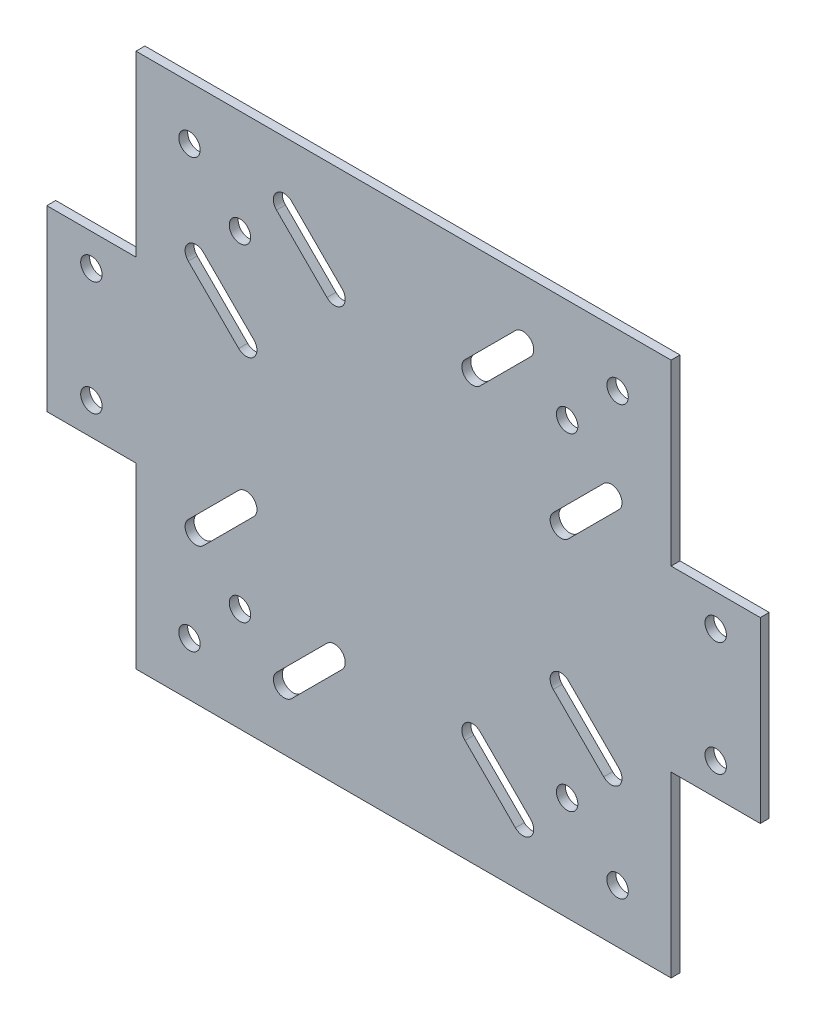
SolidWorks part; units mm, degrees
ref_plane "Front Plane" through (0, 0, 0) normal (0, 0, 1) x (1, 0, 0)
ref_plane "Top Plane" through (0, 0, 0) normal (0, 1, 0) x (1, 0, 0)
ref_plane "Right Plane" through (0, 0, 0) normal (1, 0, 0) x (0, 0, -1)
sketch "Sketch1" plane through (0, 0, 0) normal (0, 0, 1) x (1, 0, 0)
  line L0 (-91.7157, 91.7157) -> (-87.4731, 95.9584) construction
  line L1 (-150, 150) -> (150, 150)
  line L2 (-150, 150) -> (-150, -150)
  line L3 (-150, -150) -> (150, -150)
  line L4 (150, 150) -> (150, -150)
  line L5 (-150, 150) -> (150, -150) construction
  line L6 (-150, -150) -> (150, 150) construction
  line L9 (-87.4731, 95.9584) -> (-95.9584, 87.4731) construction
  line L14 (-116.4645, 66.967) -> (-150, 33.4315) construction
  line L27 (-87.4731, 95.9584) -> (-33.4315, 150) construction
  line L28 (-66.967, 116.4645) -> (-38.6827, 88.1802) construction
  line L29 (-62.7244, 120.7071) -> (-34.4401, 92.4228)
  line L30 (-71.2096, 112.2218) -> (-42.9254, 83.9376)
  line L31 (66.967, 116.4645) -> (38.6827, 88.1802) construction
  line L32 (71.2096, 112.2218) -> (42.9254, 83.9376)
  line L33 (-116.4645, 66.967) -> (-88.1802, 38.6827) construction
  line L34 (-112.2218, 71.2096) -> (-83.9376, 42.9254)
  line L35 (-120.7071, 62.7244) -> (-92.4228, 34.4401)
  line L36 (62.7244, 120.7071) -> (34.4401, 92.4228)
  line L37 (116.4645, 66.967) -> (88.1802, 38.6827) construction
  line L38 (120.7071, 62.7244) -> (92.4228, 34.4401)
  line L39 (112.2218, 71.2096) -> (83.9376, 42.9254)
  line L40 (116.4645, -66.967) -> (88.1802, -38.6827) construction
  line L41 (112.2218, -71.2096) -> (83.9376, -42.9254)
  line L42 (120.7071, -62.7244) -> (92.4228, -34.4401)
  line L43 (66.967, -116.4645) -> (38.6827, -88.1802) construction
  line L44 (62.7244, -120.7071) -> (34.4401, -92.4228)
  line L45 (71.2096, -112.2218) -> (42.9254, -83.9376)
  line L46 (-66.967, -116.4645) -> (-38.6827, -88.1802) construction
  line L47 (-71.2096, -112.2218) -> (-42.9254, -83.9376)
  line L48 (-62.7244, -120.7071) -> (-34.4401, -92.4228)
  line L49 (-116.4645, -66.967) -> (-88.1802, -38.6827) construction
  line L50 (-120.7071, -62.7244) -> (-92.4228, -34.4401)
  line L51 (-112.2218, -71.2096) -> (-83.9376, -42.9254)
  circle A0 centre (-120, 120) radius 6
  circle A1 centre (120, 120) radius 6
  circle A2 centre (-120, -120) radius 6
  circle A3 centre (120, -120) radius 6
  circle A4 centre (-91.7157, 91.7157) radius 6
  circle A5 centre (91.7157, 91.7157) radius 6
  circle A6 centre (-91.7157, -91.7157) radius 6
  circle A7 centre (91.7157, -91.7157) radius 6
  arc A24 (-62.7244, 120.7071) -> (-71.2096, 112.2218) centre (-66.967, 116.4645) ccw
  arc A25 (-42.9254, 83.9376) -> (-34.4401, 92.4228) centre (-38.6827, 88.1802) ccw
  arc A26 (-112.2218, 71.2096) -> (-120.7071, 62.7244) centre (-116.4645, 66.967) ccw
  arc A27 (71.2096, 112.2218) -> (62.7244, 120.7071) centre (66.967, 116.4645) ccw
  arc A28 (34.4401, 92.4228) -> (42.9254, 83.9376) centre (38.6827, 88.1802) ccw
  arc A29 (120.7071, 62.7244) -> (112.2218, 71.2096) centre (116.4645, 66.967) ccw
  arc A30 (83.9376, 42.9254) -> (92.4228, 34.4401) centre (88.1802, 38.6827) ccw
  arc A31 (-92.4228, 34.4401) -> (-83.9376, 42.9254) centre (-88.1802, 38.6827) ccw
  arc A32 (112.2218, -71.2096) -> (120.7071, -62.7244) centre (116.4645, -66.967) ccw
  arc A33 (92.4228, -34.4401) -> (83.9376, -42.9254) centre (88.1802, -38.6827) ccw
  arc A34 (62.7244, -120.7071) -> (71.2096, -112.2218) centre (66.967, -116.4645) ccw
  arc A35 (42.9254, -83.9376) -> (34.4401, -92.4228) centre (38.6827, -88.1802) ccw
  arc A36 (-71.2096, -112.2218) -> (-62.7244, -120.7071) centre (-66.967, -116.4645) ccw
  arc A37 (-34.4401, -92.4228) -> (-42.9254, -83.9376) centre (-38.6827, -88.1802) ccw
  arc A38 (-120.7071, -62.7244) -> (-112.2218, -71.2096) centre (-116.4645, -66.967) ccw
  arc A39 (-83.9376, -42.9254) -> (-92.4228, -34.4401) centre (-88.1802, -38.6827) ccw
  point P0 (0, 0)
  point P22 (-102.3223, 52.8249)
  point P35 (-52.8249, 102.3223)
  point P43 (52.8249, 102.3223)
  point P52 (102.3223, 52.8249)
  point P57 (102.3223, -52.8249)
  point P66 (52.8249, -102.3223)
  point P71 (-52.8249, -102.3223)
  point P77 (0, 0)
  point P81 (-102.3223, -52.8249)
  point P86 (0, 0)
  point P116 (0, 0)
  dimension "D3" = 12
  dimension "D4" = 12
  dimension "D5" = 12
  dimension "D6" = 12
  dimension "D7" = 30
  dimension "D8" = 30
  dimension "D9" = 30
  dimension "D10" = 30
  dimension "D11" = 12
  dimension "D12" = 12
  dimension "D13" = 12
  dimension "D14" = 12
  dimension "D15" = 40
  dimension "D16" = 40
  dimension "D17" = 40
  dimension "D18" = 40
  dimension "D19" = 4
  dimension "D20" = 6
  dimension "D21" = 35
  dimension "D22" = 40
  dimension "D23" = 35
  dimension "D25" = 30
  dimension "D1" = 300
  dimension "D2" = 300
  dimension "D24" = 40
extrude "Boss-Extrude1" add sketch "Sketch1" along normal blind 5
sketch "Sketch2" plane through (0, 0, 5) normal (0, 0, 1) x (1, 0, 0)
  line L0 (-150, 150) -> (-150, -150) construction
  line L3 (-200, 50) -> (-120, 50)
  line L4 (-200, 50) -> (-200, -50)
  line L5 (-200, -50) -> (-120, -50)
  line L6 (-120, 50) -> (-120, -50)
  line L9 (150, -150) -> (150, 150) construction
  line L10 (120, 50) -> (200, 50)
  line L11 (120, 50) -> (120, -50)
  line L12 (120, -50) -> (200, -50)
  line L13 (200, 50) -> (200, -50)
  point P0 (-150, 0)
  point P7 (150, 0)
  dimension "D1" = 100
  dimension "D2" = 100
  dimension "D3" = 80
  dimension "D4" = 80
extrude "Boss-Extrude2" add sketch "Sketch2" against normal blind 5
sketch "Sketch3" plane through (0, 0, 5) normal (0, 0, 1) x (1, 0, 0)
  line L0 (-175, 50) -> (-175, -50) construction
  line L1 (-150, 50) -> (-200, 50) construction
  line L2 (-200, -50) -> (-150, -50) construction
  line L3 (175, 50) -> (175, -50) construction
  line L4 (200, 50) -> (150, 50) construction
  line L5 (150, -50) -> (200, -50) construction
  circle A0 centre (-175, 32) radius 6
  circle A1 centre (-175, -32) radius 6
  circle A2 centre (175, 32) radius 6
  circle A3 centre (175, -32) radius 6
  dimension "D1" = 18
  dimension "D2" = 18
  dimension "D3" = 18
  dimension "D4" = 18
  dimension "D5" = 12
  dimension "D6" = 12
  dimension "D7" = 12
  dimension "D8" = 12
  dimension "D9" = 64
extrude "Cut-Extrude1" cut sketch "Sketch3" against normal blind 264
